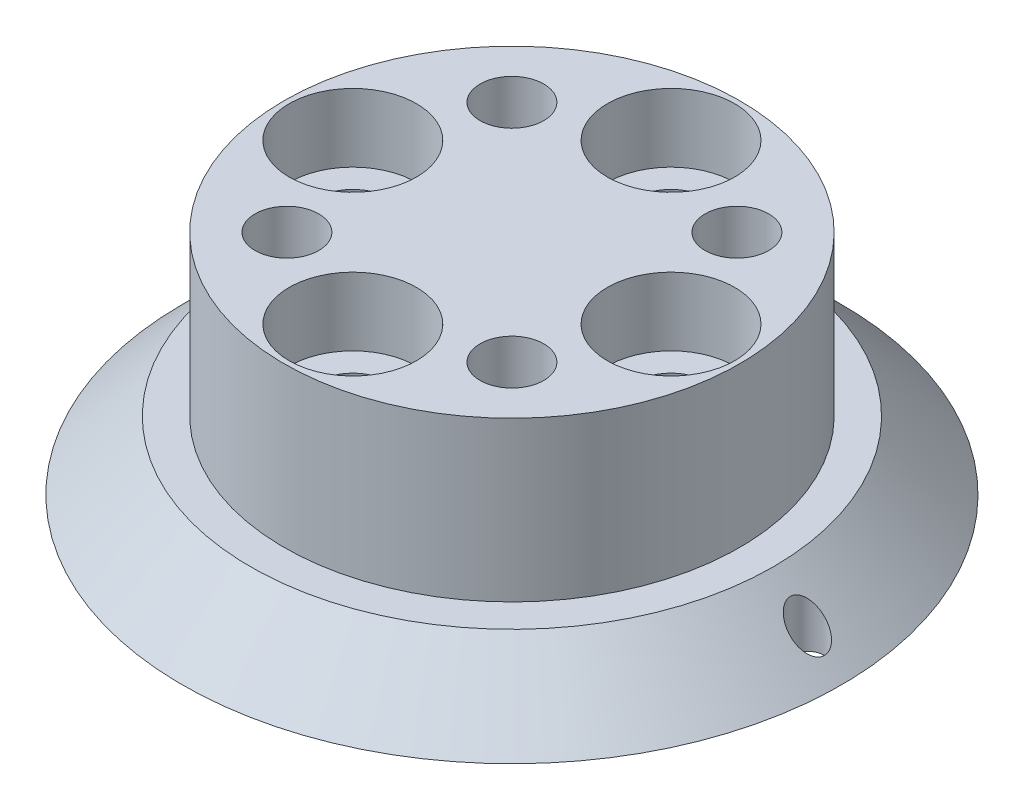
SolidWorks part; units mm, degrees
ref_plane "Front Plane" through (0, 0, 0) normal (0, 0, 1) x (1, 0, 0)
ref_plane "Top Plane" through (0, 0, 0) normal (0, 1, 0) x (1, 0, 0)
ref_plane "Right Plane" through (0, 0, 0) normal (1, 0, 0) x (0, 0, -1)
sketch "Sketch1" plane through (0, 0, 0) normal (0, 0, 1) x (1, 0, 0)
  line L0 (14.5, 0) -> (11.5, 3)
  line L1 (11.5, 3) -> (10.025, 3)
  line L2 (10.025, 3) -> (10.025, 10)
  line L3 (10.025, 10) -> (0, 10)
  line L4 (14.5, 0) -> (0, 0)
  line L5 (0, 10) -> (0, 0) construction
  line L6 (0, 10) -> (0, 0)
  dimension "D1" = 20.05
  dimension "D2" = 23
  dimension "D3" = 3
  dimension "D4" = 3
  dimension "D5" = 7
revolve "Revolve1" add sketch "Sketch1" angle 360 about L5
sketch "Sketch2" plane through (0, 10, 0) normal (0, 1, 0) x (1, 0, 0)
  line L0 (0, 0) -> (0, 7) construction
  circle A0 centre (0, 7) radius 1.4
  circle A1 centre (4.9497, 4.9497) radius 1.4
  circle A2 centre (7, 0) radius 1.4
  circle A3 centre (4.9497, -4.9497) radius 1.4
  circle A4 centre (0, -7) radius 1.4
  circle A5 centre (-4.9497, -4.9497) radius 1.4
  circle A6 centre (-7, 0) radius 1.4
  circle A7 centre (-4.9497, 4.9497) radius 1.4
  point P13 (0, 0)
  dimension "D1" = 2.8
  dimension "D2" = 7
  dimension "D3" = 8
extrude "Cut-Extrude1" cut sketch "Sketch2" against normal through all
hole_wizard "CBORE for M5 Hex Head Bolt1" positions "3DSketch1" profile "Sketch3" counterbore size "M5" standard "ANSI Metric" end condition through all
sketch3d "3DSketch1"
  line L0 (0, 0, -7) -> (0, 10, -7) construction
  line L1 (-7, 0, 0) -> (-7, 10, 0) construction
  line L2 (0, 0, 7) -> (0, 10, 7) construction
  line L3 (7, 0, 0) -> (7, 10, 0) construction
  point P0 (0, 10, -7)
  point P4 (-7, 10, 0)
  point P8 (0, 10, 7)
  point P12 (7, 10, 0)
sketch "Sketch3" plane through (0, 10, -7) normal (1, 0, 0) x (0, 0, 1)
  line L0 (0, 0) -> (0, 10)
  line L1 (0, 10) -> (1.6, 10)
  line L3 (1.6, 10) -> (1.6, 3)
  line L4 (1.6, 3) -> (2.8, 3)
  line L5 (2.8, 3) -> (2.8, 0)
  line L7 (2.8, 0) -> (0, 0)
  line L11 (0, -6.35) -> (0, 107.95) construction
  dimension "Thru Hole Dia." = 3.2
  dimension "Thru Hole Depth" = 10
  dimension "C'Bore Dia." = 5.6
  dimension "C'Bore Depth" = 3
sketch "Sketch4" plane through (0, 0, 0) normal (0, 1, 0) x (1, 0, 0)
  line L0 (0, 0) -> (13, 0) construction
  circle A0 centre (13, 0) radius 0.75
  dimension "D1" = 1.5
  dimension "D2" = 13
extrude "Cut-Extrude3" cut sketch "Sketch4" along normal through all
